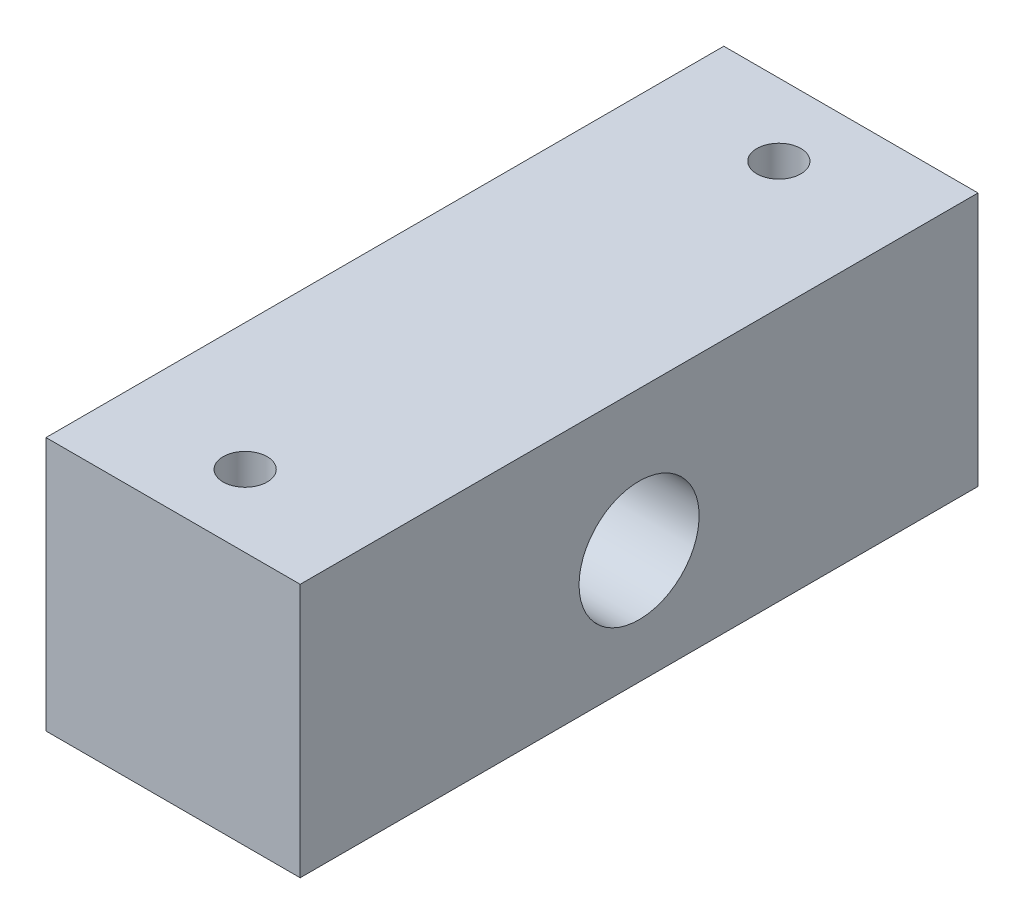
SolidWorks part; units mm, degrees
ref_plane "Front" through (0, 0, 0) normal (0, 0, 1) x (1, 0, 0)
ref_plane "Top" through (0, 0, 0) normal (0, 1, 0) x (1, 0, 0)
ref_plane "Right" through (0, 0, 0) normal (1, 0, 0) x (0, 0, -1)
sketch "Sketch1" plane through (0, 0, 0) normal (0, 0, 1) x (1, 0, 0)
  line L1 (-9.525, 9.525) -> (9.525, 9.525)
  line L2 (-9.525, 9.525) -> (-9.525, -9.525)
  line L3 (-9.525, -9.525) -> (9.525, -9.525)
  line L4 (9.525, 9.525) -> (9.525, -9.525)
  line L5 (-9.525, 9.525) -> (9.525, -9.525) construction
  line L6 (-9.525, -9.525) -> (9.525, 9.525) construction
  point P0 (0, 0)
  dimension "D1" = 19.05
extrude "Boss-Extrude1" add sketch "Sketch1" along normal mid plane 50.8
hole_wizard "Tap Drill for M4x0.7 Tap1" positions "Sketch2" profile "Sketch3" hole size "M4x0.7" standard "ANSI Metric" end condition through all
sketch "Sketch2" plane through (0, 9.525, 0) normal (0, 1, 0) x (1, 0, 0)
  line L0 (0, 20) -> (0, -20)
  point P1 (0, 20)
  point P2 (0, -20)
  dimension "D1" = 40
sketch "Sketch3" plane through (0, 9.525, -20) normal (1, 0, 0) x (0, 0, 1)
  line L0 (0, 0) -> (0, 19.05)
  line L1 (0, 19.05) -> (1.65, 19.05)
  line L2 (1.65, 19.05) -> (1.65, 0)
  line L5 (1.65, 0) -> (0, 0)
  line L11 (0, -6.35) -> (0, 107.95) construction
  dimension "Thru Hole Dia." = 3.3
  dimension "Thru Hole Depth" = 19.05
hole_wizard "M8 Clearance Hole1" positions "Sketch4" profile "Sketch5" hole size "M8" standard "ANSI Metric" end condition through all
sketch "Sketch4" plane through (-9.525, 0, 0) normal (-1, 0, 0) x (0, 0, 1)
  line L0 (25.4, 9.525) -> (-25.4, 9.525) construction
  point P0 (0, -0.975)
  point P5 (0, 0)
  dimension "D1" = 10.5
sketch "Sketch5" plane through (-9.525, -0.975, 0) normal (0, 1, 0) x (0, 0, 1)
  line L0 (0, 0) -> (0, 19.05)
  line L1 (0, 19.05) -> (4.5, 19.05)
  line L2 (4.5, 19.05) -> (4.5, 0)
  line L5 (4.5, 0) -> (0, 0)
  line L11 (0, -6.35) -> (0, 107.95) construction
  dimension "Thru Hole Dia." = 9
  dimension "Thru Hole Depth" = 19.05
